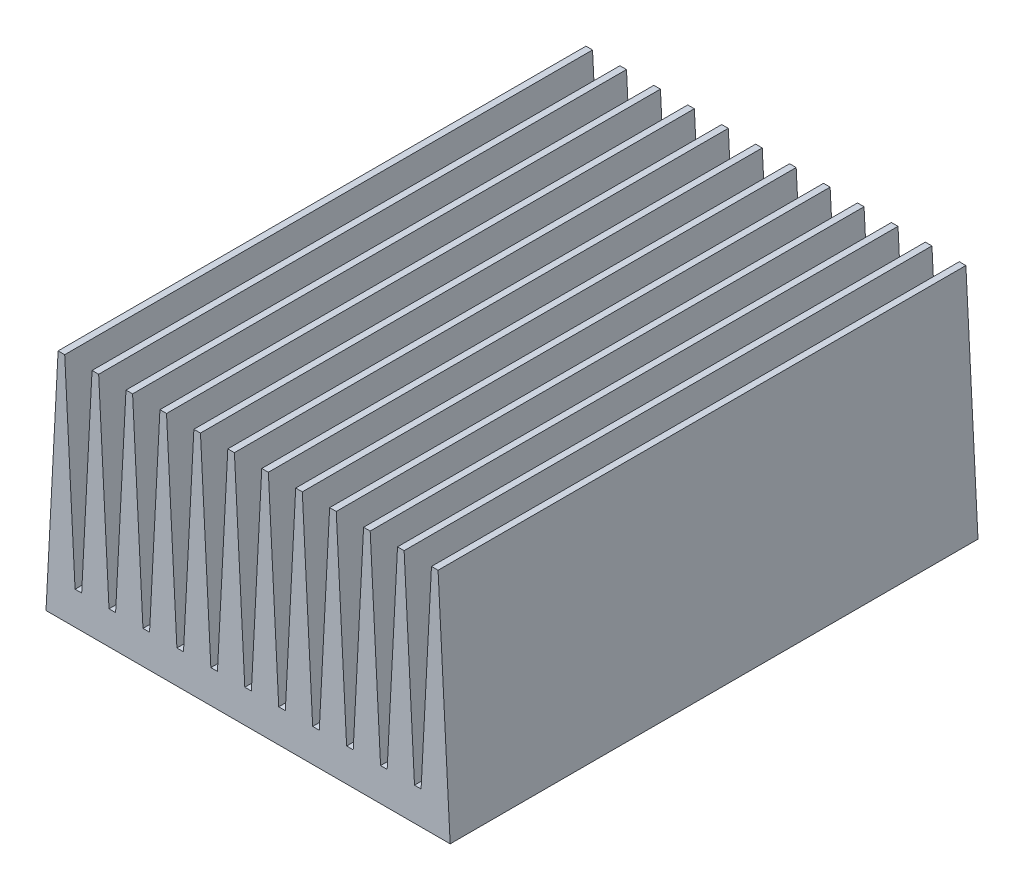
SolidWorks part; units mm, degrees
ref_plane "Front Plane" through (0, 0, 0) normal (0, 0, 1) x (1, 0, 0)
ref_plane "Top Plane" through (0, 0, 0) normal (0, 1, 0) x (1, 0, 0)
ref_plane "Right Plane" through (0, 0, 0) normal (1, 0, 0) x (0, 0, -1)
sketch "Sketch1" plane through (0, 0, 0) normal (0, 0, 1) x (1, 0, 0)
  line L0 (0, 0) -> (12.7, 0)
  line L1 (12.7, 0) -> (52.6347, 762)
  line L2 (52.6347, 762) -> (78.0347, 762)
  line L3 (0, 0) -> (0, -127)
  line L4 (0, -127) -> (130.6695, -127)
  line L5 (78.0347, 762) -> (117.9695, 0)
  line L6 (117.9695, 0) -> (130.6695, 0)
  line L7 (130.6695, 0) -> (130.6695, -127)
  line L8 (65.3347, 762) -> (65.3347, -127) construction
  dimension "D1" = 25.4
  dimension "D2" = 87
  dimension "D3" = 12.7
  dimension "D4" = 127
  dimension "D5" = 889
  dimension "D6" = 130.6695
extrude "Boss-Extrude1" add sketch "Sketch1" against normal blind 2032
pattern_linear "LPattern1" count 6 spacing 130.6678 along (-1, 0, 0) count 7 spacing 130.6678 along (1, 0, 0) of "Boss-Extrude1"
sketch "Sketch2" plane through (0, 0, 0) normal (0, 0, 1) x (1, 0, 0)
  line L2 (-653.3388, -127) -> (914.676, -127) construction
  line L7 (-640.6388, 0) -> (-647.2946, -127)
  line L8 (-600.7041, 762) -> (-640.6388, 0) construction
  line L9 (-653.3388, 0) -> (-653.3388, -127) construction
  line L10 (-640.6388, 0) -> (-653.3388, 0) construction
  line L11 (-653.3388, 0) -> (-653.3388, -127)
  line L12 (-640.6388, 0) -> (-653.3388, 0)
  line L14 (-653.3388, -127) -> (-647.2946, -127)
  line L15 (901.976, 0) -> (908.6318, -127)
  line L16 (914.676, -127) -> (914.676, 0)
  line L17 (914.676, 0) -> (901.976, 0)
  line L18 (908.6318, -127) -> (914.676, -127)
  point P22 (0, 0)
extrude "Cut-Extrude1" cut sketch "Sketch2" against normal blind 2032
